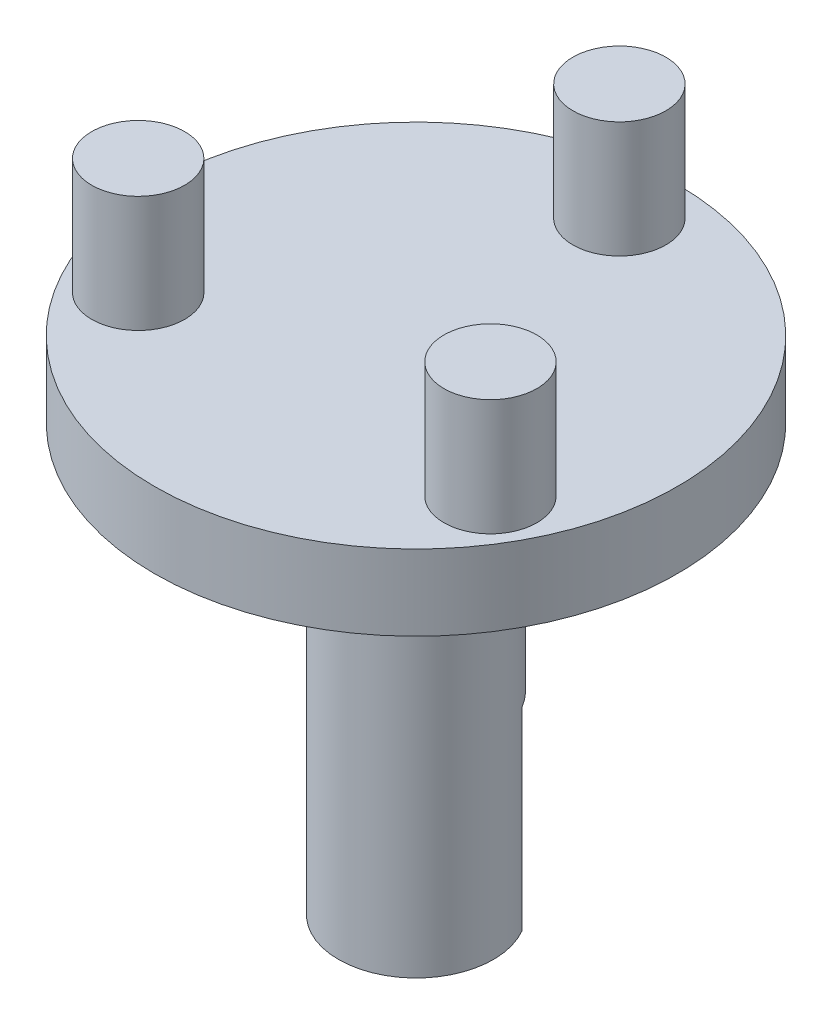
SolidWorks part; units mm, degrees
ref_plane "前视基准面" through (0, 0, 0) normal (0, 0, 1) x (1, 0, 0)
ref_plane "上视基准面" through (0, 0, 0) normal (0, 1, 0) x (1, 0, 0)
ref_plane "右视基准面" through (0, 0, 0) normal (1, 0, 0) x (0, 0, -1)
sketch "草图1" plane through (0, 0, 0) normal (0, 1, 0) x (1, 0, 0)
  circle A0 centre (0, 0) radius 13.5
  dimension "D1" = 27
extrude "凸台-拉伸1" add sketch "草图1" along normal blind 3.9
sketch "草图2" plane through (0, 3.9, 0) normal (0, 1, 0) x (1, 0, 0)
  line L0 (0, 0) -> (0, 10.5) construction
  circle A0 centre (0, 0) radius 10.5 construction
  circle A1 centre (0, 10.5) radius 2.4
  circle A2 centre (9.0933, -5.25) radius 2.4
  circle A3 centre (-9.0933, -5.25) radius 2.4
  point P12 (0, 0)
  dimension "D1" = 21
  dimension "D2" = 4.8
  dimension "D3" = 3
extrude "凸台-拉伸2" add sketch "草图2" along normal blind 6
sketch "草图3" plane through (0, 0, 0) normal (0, -1, 0) x (1, 0, 0)
  circle A0 centre (0, 0) radius 4
  dimension "D1" = 8
extrude "凸台-拉伸3" add sketch "草图3" along normal blind 7
sketch "草图4" plane through (0, 0, 0) normal (0, -1, 0) x (1, 0, 0)
  circle A0 centre (0, 0) radius 5.5
  dimension "D1" = 11
extrude "凸台-拉伸4" add sketch "草图4" along normal blind 1
sketch "草图5" plane through (0, -7, 0) normal (0, -1, 0) x (1, 0, 0)
  circle A1 centre (0, 0) radius 4
  circle A2 centre (0, 0) radius 4
  dimension "D1" = 0
extrude "凸台-拉伸5" add sketch "草图5" along normal blind 15
sketch "草图6" plane through (0, -22, 0) normal (0, -1, 0) x (1, 0, 0)
  line L0 (3.4641, -2) -> (-3.4641, -2)
  line L1 (-3.4641, -2) -> (0, 0) construction
  line L2 (0, 0) -> (3.4641, -2) construction
  circle A0 centre (0, 0) radius 4 construction
  circle A2 centre (0, 0) radius 4
  arc A3 (-3.4641, -2) -> (3.4641, -2) centre (0, 0) ccw
  dimension "D1" = 120
  dimension "D2" = 0
extrude "切除-拉伸1" cut sketch "草图6" against normal blind 10
sketch "草图7" plane through (0, 0, -2) normal (0, 0, -1) x (-1, 0, 0)
  line L0 (0, -22) -> (0, -12) construction
  line L1 (-3.4641, -22) -> (3.4641, -22) construction
  line L2 (-3.4641, -12) -> (3.4641, -12) construction
  line L3 (-13.5, 0) -> (13.5, 0) construction
  circle A0 centre (0, -15.5) radius 1.5
  dimension "D1" = 3
  dimension "D2" = 15.5
extrude "切除-拉伸2" cut sketch "草图7" against normal blind 1
